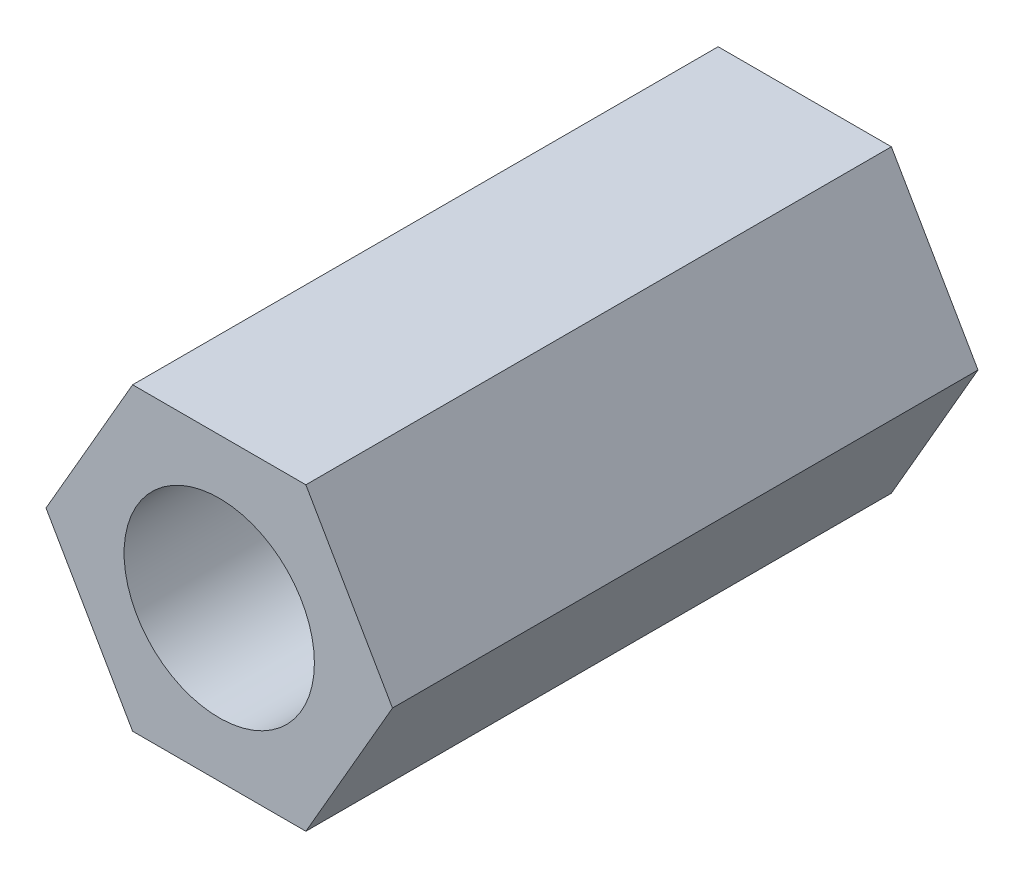
SolidWorks part; units mm, degrees
ref_plane "前视基准面" through (0, 0, 0) normal (0, 0, 1) x (1, 0, 0)
ref_plane "上视基准面" through (0, 0, 0) normal (0, 1, 0) x (1, 0, 0)
ref_plane "右视基准面" through (0, 0, 0) normal (1, 0, 0) x (0, 0, -1)
sketch "草图1" plane through (0, 0, 0) normal (0, 0, 1) x (1, 0, 0)
  line L1 (-23.6714, 0) -> (-11.8357, -20.5)
  line L2 (-11.8357, -20.5) -> (11.8357, -20.5)
  line L3 (11.8357, -20.5) -> (23.6714, 0)
  line L4 (23.6714, 0) -> (11.8357, 20.5)
  line L5 (11.8357, 20.5) -> (-11.8357, 20.5)
  line L6 (-11.8357, 20.5) -> (-23.6714, 0)
  circle A0 centre (0, 0) radius 20.5 construction
  dimension "D1" = 41
  dimension "D2" = 47.3427
extrude "凸台-拉伸1" add sketch "草图1" along normal blind 80
sketch "草图2" plane through (0, 0, 80) normal (0, 0, 1) x (1, 0, 0)
  circle A0 centre (0, 0) radius 13
  dimension "D1" = 26
extrude "切除-拉伸1" cut sketch "草图2" against normal blind 37
sketch "草图3" plane through (0, 0, 43) normal (0, 0, 1) x (1, 0, 0)
  circle A0 centre (0, 0) radius 11.1
  dimension "D1" = 22.2
extrude "切除-拉伸2" cut sketch "草图3" against normal blind 63
